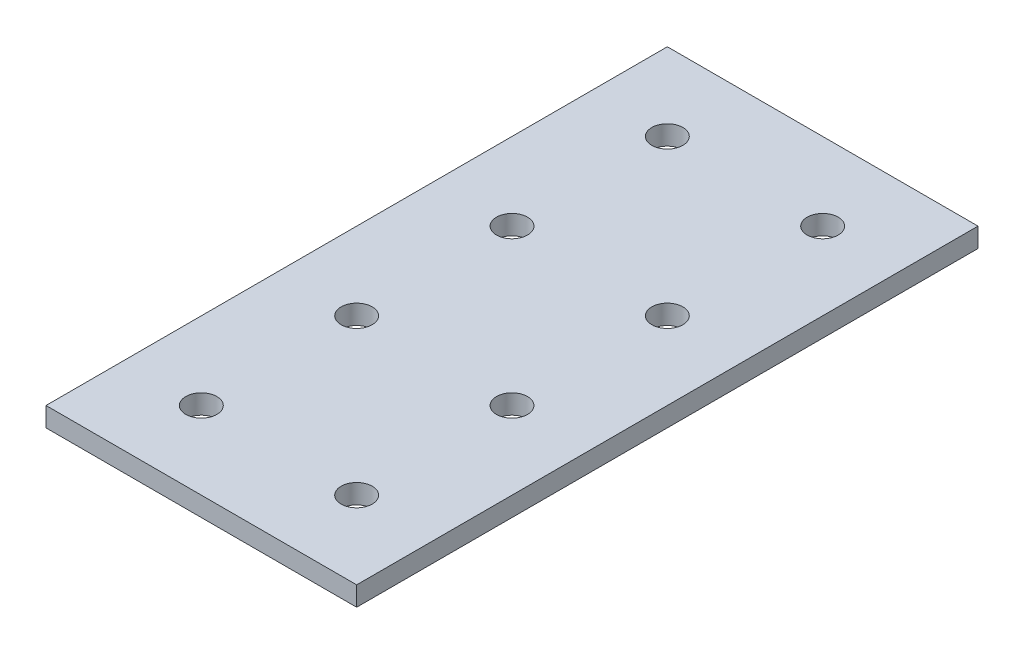
SolidWorks part; units mm, degrees
ref_plane "Front Plane" through (0, 0, 0) normal (0, 0, 1) x (1, 0, 0)
ref_plane "Top Plane" through (0, 0, 0) normal (0, 1, 0) x (1, 0, 0)
ref_plane "Right Plane" through (0, 0, 0) normal (1, 0, 0) x (0, 0, -1)
sketch "Sketch1" plane through (0, 0, 0) normal (0, 1, 0) x (1, 0, 0)
  line L1 (-38.1, -50.8) -> (12.7, -50.8)
  line L2 (-38.1, -50.8) -> (-38.1, 50.8)
  line L3 (-38.1, 50.8) -> (12.7, 50.8)
  line L5 (-38.1, -50.8) -> (12.7, 16.9333) construction
  line L6 (-38.1, 50.8) -> (12.7, -16.9333) construction
  line L7 (12.7, 0) -> (12.7, 50.8)
  line L8 (12.7, 0) -> (12.7, -50.8)
  point P0 (0, 0)
  dimension "D1" = 101.6
  dimension "D3" = 50.8
extrude "Boss-Extrude1" add sketch "Sketch1" along normal blind 3.175
sketch "Sketch2" plane through (0, 3.175, 0) normal (0, 1, 0) x (1, 0, 0)
  line L0 (12.7, 50.8) -> (-38.1, 50.8) construction
  line L1 (-38.1, 50.8) -> (-38.1, -50.8) construction
  circle A0 centre (-25.4, 38.1) radius 2.54
  circle A1 centre (-25.4, 12.7) radius 2.54
  circle A2 centre (-25.4, -12.7) radius 2.54
  circle A3 centre (-25.4, -38.1) radius 2.54
  circle A4 centre (0, 12.7) radius 2.54
  circle A5 centre (0, -12.7) radius 2.54
  circle A6 centre (0, -38.1) radius 2.54
  circle A7 centre (0, 38.1) radius 2.54
  dimension "D1" = 12.7
  dimension "D2" = 12.7
  dimension "D3" = 4
  dimension "D4" = 2
extrude "Cut-Extrude1" cut sketch "Sketch2" against normal up to surface (3.175 mm away) up to face at (-12.7, 0, 0)
